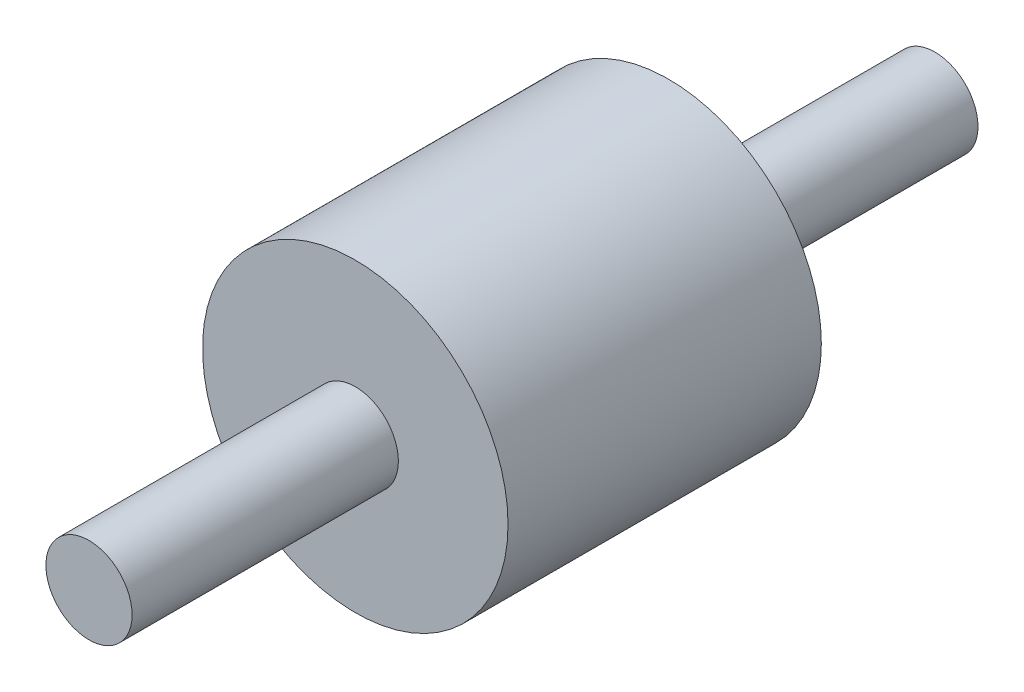
SolidWorks part; units mm, degrees
ref_plane "Front Plane" through (0, 0, 0) normal (0, 0, 1) x (1, 0, 0)
ref_plane "Top Plane" through (0, 0, 0) normal (0, 1, 0) x (1, 0, 0)
ref_plane "Right Plane" through (0, 0, 0) normal (1, 0, 0) x (0, 0, -1)
sketch "Sketch1" plane through (0, 0, 0) normal (0, 0, 1) x (1, 0, 0)
  circle A0 centre (0, 0) radius 9.75
  dimension "D1" = 19.5
extrude "Boss-Extrude1" add sketch "Sketch1" along normal blind 20
sketch "Sketch2" plane through (0, 0, 20) normal (0, 0, 1) x (1, 0, 0)
  circle A0 centre (0, 0) radius 2.75
  dimension "D1" = 5.5
extrude "Boss-Extrude2" add sketch "Sketch2" along normal blind 17 and the other way blind 37
